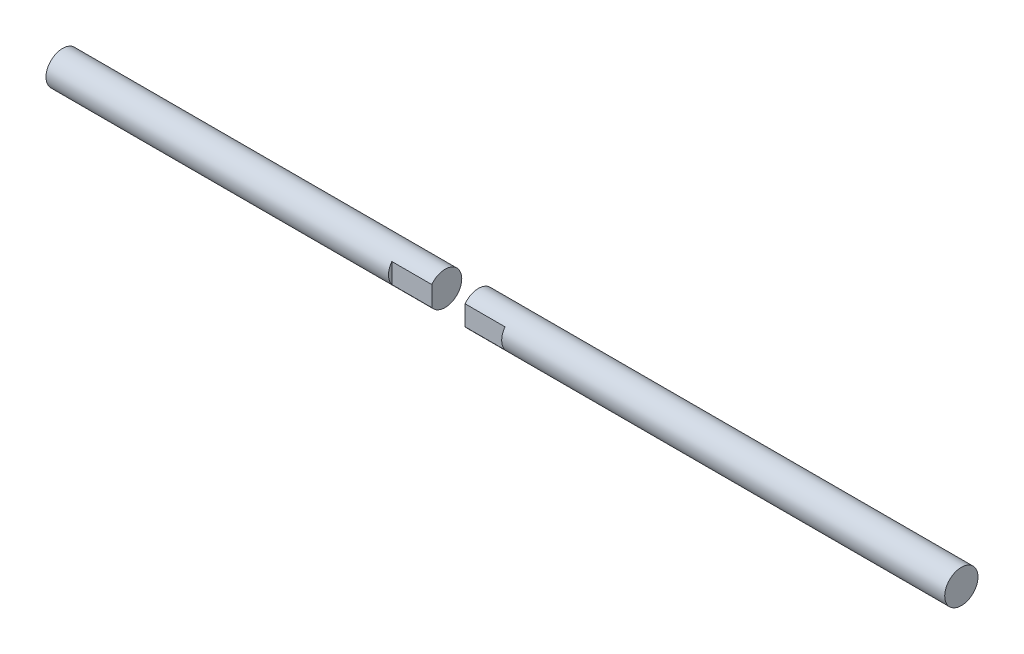
SolidWorks part; units mm, degrees
ref_plane "Front Plane" through (0, 0, 0) normal (0, 0, 1) x (1, 0, 0)
ref_plane "Top Plane" through (0, 0, 0) normal (0, 1, 0) x (1, 0, 0)
ref_plane "Right Plane" through (0, 0, 0) normal (1, 0, 0) x (0, 0, -1)
sketch "Sketch1" plane through (0, 0, 0) normal (1, 0, 0) x (0, 0, -1)
  circle A0 centre (0, 0) radius 3.175
extrude "Boss-Extrude1" add sketch "Sketch1" along normal blind 165.1
sketch "Sketch2" plane through (0, 0, 0) normal (0, 0, 1) x (1, 0, 0)
  line L1 (72.965, 7.7951) -> (79.315, 7.7951)
  line L2 (72.965, 7.7951) -> (72.965, -7.0212)
  line L3 (72.965, -7.0212) -> (79.315, -7.0212)
  line L4 (79.315, 7.7951) -> (79.315, -7.0212)
extrude "Cut-Extrude1" cut sketch "Sketch2" against normal through all and the other way through all
ref_plane "Plane1" through (0, 0, 2.54) normal (0, 0, 1) x (1, 0, 0)
sketch "Sketch3" plane through (0, 0, 2.54) normal (0, 0, 1) x (1, 0, 0)
  line L0 (79.315, 3.175) -> (79.315, -3.175) construction
  line L1 (65.345, 5.8289) -> (86.935, 5.8289)
  line L2 (65.345, 5.8289) -> (65.345, -5.051)
  line L3 (65.345, -5.051) -> (86.935, -5.051)
  line L4 (86.935, 5.8289) -> (86.935, -5.051)
  line L5 (72.965, -3.175) -> (72.965, 3.175) construction
  dimension "D1" = 7.62
  dimension "D2" = 7.62
extrude "Cut-Extrude2" cut sketch "Sketch3" along normal blind 12.954
sketch "Sketch4" plane through (165.1, 0, 0) normal (1, 0, 0) x (0, 0, -1)
  circle A0 centre (0, 0) radius 3.175
extrude "Boss-Extrude2" add sketch "Sketch4" along normal blind 6.35
